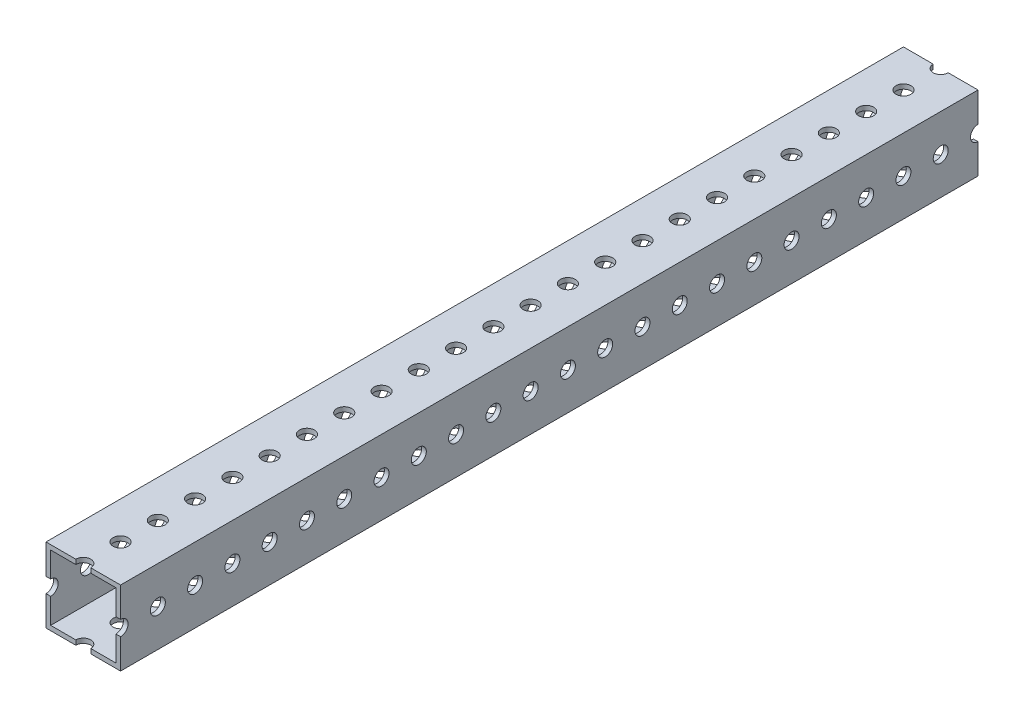
SolidWorks part; units mm, degrees
ref_plane "Front Plane" through (0, 0, 0) normal (0, 0, 1) x (1, 0, 0)
ref_plane "Top Plane" through (0, 0, 0) normal (0, 1, 0) x (1, 0, 0)
ref_plane "Right Plane" through (0, 0, 0) normal (1, 0, 0) x (0, 0, -1)
sketch "Sketch1" plane through (0, 0, 0) normal (0, 0, 1) x (1, 0, 0)
  line L1 (-12.7, 12.7) -> (12.7, 12.7)
  line L2 (-12.7, 12.7) -> (-12.7, -12.7)
  line L3 (-12.7, -12.7) -> (12.7, -12.7)
  line L4 (12.7, 12.7) -> (12.7, -12.7)
  line L5 (-12.7, 12.7) -> (12.7, -12.7) construction
  line L6 (-12.7, -12.7) -> (12.7, 12.7) construction
  line L7 (-11.1125, 11.1125) -> (11.1125, 11.1125)
  line L8 (-11.1125, 11.1125) -> (-11.1125, -11.1125)
  line L9 (-11.1125, -11.1125) -> (11.1125, -11.1125)
  line L10 (11.1125, 11.1125) -> (11.1125, -11.1125)
  line L11 (-11.1125, 11.1125) -> (11.1125, -11.1125) construction
  line L12 (-11.1125, -11.1125) -> (11.1125, 11.1125) construction
  point P0 (0, 0)
  point P6 (0, 0)
  dimension "D1" = 25.4
  dimension "D2" = 25.4
  dimension "D3" = 1.5875
  dimension "D4" = 1.5875
extrude "Boss-Extrude1" add sketch "Sketch1" along normal blind 292.1
sketch "Sketch2" plane through (0, 12.7, 0) normal (0, 1, 0) x (1, 0, 0)
  line L0 (0, 0) -> (0, -12.7) construction
  circle A0 centre (0, 0) radius 2.5527
  circle A1 centre (0, -12.7) radius 2.5527
  circle A2 centre (0, -25.4) radius 2.5527
  circle A3 centre (0, -38.1) radius 2.5527
  circle A4 centre (0, -50.8) radius 2.5527
  circle A5 centre (0, -63.5) radius 2.5527
  circle A6 centre (0, -76.2) radius 2.5527
  circle A7 centre (0, -88.9) radius 2.5527
  circle A8 centre (0, -101.6) radius 2.5527
  circle A9 centre (0, -114.3) radius 2.5527
  circle A10 centre (0, -127) radius 2.5527
  circle A11 centre (0, -139.7) radius 2.5527
  circle A12 centre (0, -152.4) radius 2.5527
  circle A13 centre (0, -165.1) radius 2.5527
  circle A14 centre (0, -177.8) radius 2.5527
  circle A15 centre (0, -190.5) radius 2.5527
  circle A16 centre (0, -203.2) radius 2.5527
  circle A17 centre (0, -215.9) radius 2.5527
  circle A18 centre (0, -228.6) radius 2.5527
  circle A19 centre (0, -241.3) radius 2.5527
  circle A20 centre (0, -254) radius 2.5527
  circle A21 centre (0, -266.7) radius 2.5527
  circle A22 centre (0, -279.4) radius 2.5527
  circle A23 centre (0, -292.1) radius 2.5527
  circle A24 centre (0, -304.8) radius 2.5527
  circle A25 centre (0, -317.5) radius 2.5527
  dimension "D1" = 5.1054
  dimension "D3" = 12.7
  dimension "D2" = 26
extrude "Cut-Extrude1" cut sketch "Sketch2" against normal through all
sketch "Sketch3" plane through (12.7, 0, 0) normal (1, 0, 0) x (0, 0, -1)
  line L0 (0, -12.7) -> (0, 12.7) construction
  line L1 (0, 0) -> (-12.7, 0) construction
  circle A0 centre (0, 0) radius 2.5527
  circle A1 centre (-12.7, 0) radius 2.5527
  circle A2 centre (-25.4, 0) radius 2.5527
  circle A3 centre (-38.1, 0) radius 2.5527
  circle A4 centre (-50.8, 0) radius 2.5527
  circle A5 centre (-63.5, 0) radius 2.5527
  circle A6 centre (-76.2, 0) radius 2.5527
  circle A7 centre (-88.9, 0) radius 2.5527
  circle A8 centre (-101.6, 0) radius 2.5527
  circle A9 centre (-114.3, 0) radius 2.5527
  circle A10 centre (-127, 0) radius 2.5527
  circle A11 centre (-139.7, 0) radius 2.5527
  circle A12 centre (-152.4, 0) radius 2.5527
  circle A13 centre (-165.1, 0) radius 2.5527
  circle A14 centre (-177.8, 0) radius 2.5527
  circle A15 centre (-190.5, 0) radius 2.5527
  circle A16 centre (-203.2, 0) radius 2.5527
  circle A17 centre (-215.9, 0) radius 2.5527
  circle A18 centre (-228.6, 0) radius 2.5527
  circle A19 centre (-241.3, 0) radius 2.5527
  circle A20 centre (-254, 0) radius 2.5527
  circle A21 centre (-266.7, 0) radius 2.5527
  circle A22 centre (-279.4, 0) radius 2.5527
  circle A23 centre (-292.1, 0) radius 2.5527
  circle A24 centre (-304.8, 0) radius 2.5527
  circle A25 centre (-317.5, 0) radius 2.5527
  dimension "D1" = 5.1054
  dimension "D3" = 12.7
  dimension "D2" = 26
extrude "Cut-Extrude2" cut sketch "Sketch3" against normal through all
